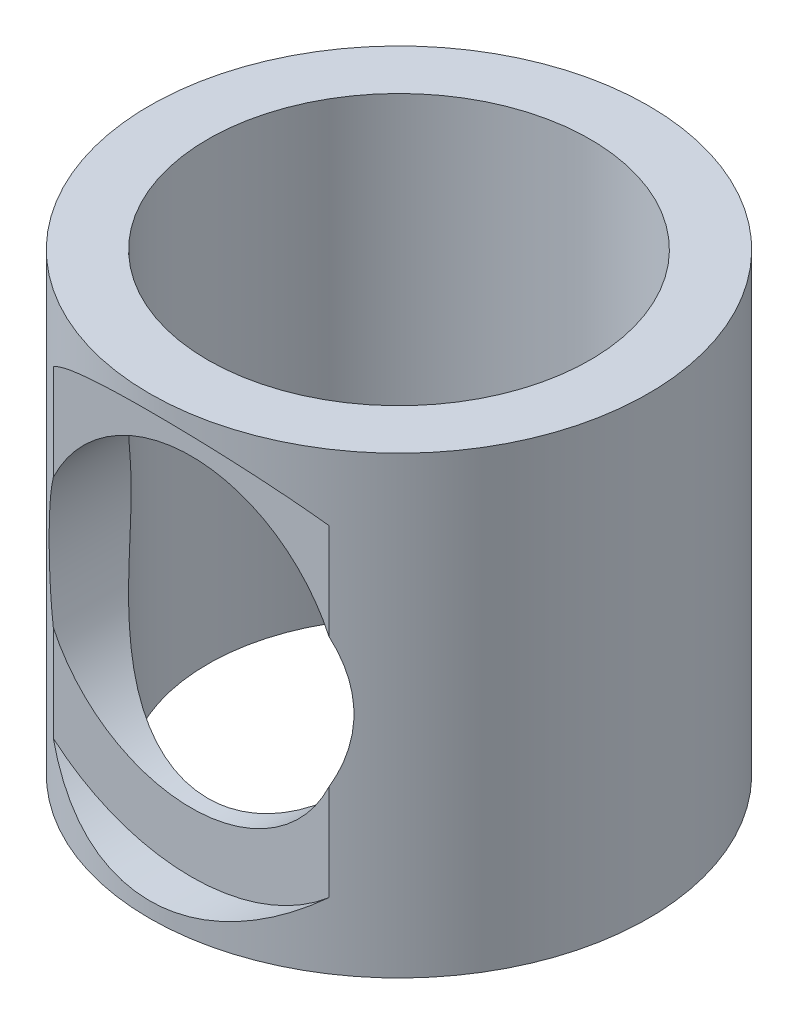
SolidWorks part; units mm, degrees
material "OMD-98"
ref_plane "Front Plane" through (0, 0, 0) normal (0, 0, 1) x (1, 0, 0)
ref_plane "Top Plane" through (0, 0, 0) normal (0, 1, 0) x (1, 0, 0)
ref_plane "Right Plane" through (0, 0, 0) normal (1, 0, 0) x (0, 0, -1)
sketch "Sketch1" plane through (0, 0, 0) normal (0, 1, 0) x (1, 0, 0)
  circle A0 centre (0, 0) radius 9
  circle A1 centre (0, 0) radius 6.9
  dimension "D1" = 18
  dimension "D2" = 13.8
extrude "Boss-Extrude1" add sketch "Sketch1" against normal blind 16.4
sketch "Sketch3" plane through (0, 0, 0) normal (0, 0, 1) x (1, 0, 0)
  line L1 (6.9, 0) -> (-6.9, 0) construction
  circle A0 centre (0, -8.2) radius 7.65
  point P4 (0, -15.85)
  dimension "D1" = 15.3
  dimension "D2" = 8.2
extrude "Cut-Extrude5" cut sketch "Sketch3" along normal through all from offset 7.5
sketch "Sketch6" plane through (0, 0, 7.5) normal (0, 0, 1) x (1, 0, 0)
  line L2 (9, 0) -> (-9, 0) construction
  circle A0 centre (0, -8.2) radius 5.5
  dimension "D1" = 11
  dimension "D2" = 8.2
extrude "Cut-Extrude6" cut sketch "Sketch6" against normal blind 7 and the other way through all
